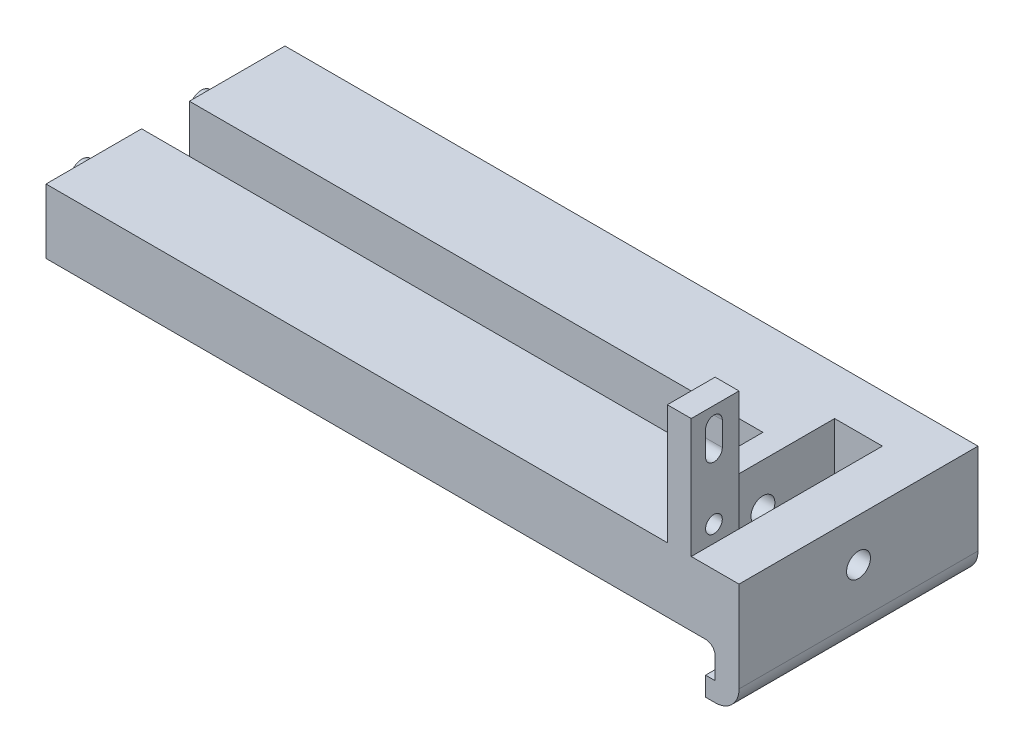
SolidWorks part; units mm, degrees
ref_plane "Front Plane" through (0, 0, 0) normal (0, 0, 1) x (1, 0, 0)
ref_plane "Top Plane" through (0, 0, 0) normal (0, 1, 0) x (1, 0, 0)
ref_plane "Right Plane" through (0, 0, 0) normal (1, 0, 0) x (0, 0, -1)
sketch "Sketch1" plane through (0, 0, 0) normal (0, 0, 1) x (1, 0, 0)
  line L0 (0, 0) -> (-140, 0)
  line L1 (-140, 0) -> (-140, 13.5)
  line L2 (-140, 13.5) -> (0, 13.5)
  line L3 (0, 13.5) -> (0, 0)
  dimension "D1" = 140
  dimension "D2" = 13.5
extrude "Boss-Extrude1" add sketch "Sketch1" along normal blind 50
sketch "Sketch2" plane through (-140, 0, 0) normal (-1, 0, 0) x (0, 0, 1)
  line L0 (50, 13.5) -> (50, 0) construction
  line L1 (12.5, 6.75) -> (25, 6.75) construction
  line L2 (25, 6.75) -> (37.5, 6.75) construction
  line L3 (37.5, 6.75) -> (50, 6.75) construction
  line L4 (0, 6.75) -> (12.5, 6.75) construction
  line L5 (0, 13.5) -> (0, 0) construction
  circle A0 centre (12.5, 6.75) radius 2.5
  circle A2 centre (37.5, 6.75) radius 2.5
  point P9 (50, 6.75)
  dimension "D1" = 5
  dimension "D2" = 5
extrude "Boss-Extrude2" add sketch "Sketch2" along normal blind 5
sketch "Sketch6" plane through (0, 0, 0) normal (1, 0, 0) x (0, 0, -1)
  line L0 (-50, 0) -> (-50, 13.5) construction
  line L1 (0, 13.5) -> (-50, 13.5)
  line L2 (0, 13.5) -> (0, -10.5)
  line L3 (0, -10.5) -> (-50, -10.5)
  line L4 (-50, 13.5) -> (-50, -10.5)
  dimension "D1" = 24
extrude "Boss-Extrude4" add sketch "Sketch6" along normal blind 5
sketch "Sketch4" plane through (0, 13.5, 0) normal (0, 1, 0) x (1, 0, 0)
  line L1 (-5, -40) -> (-15, -40)
  line L2 (-5, -40) -> (-5, -10)
  line L3 (-5, -10) -> (-15, -10)
  line L4 (-15, -40) -> (-15, -10)
  line L7 (5, 0) -> (-140, 0) construction
  line L8 (5, -50) -> (-140, -50) construction
  line L9 (5, 0) -> (5, -50) construction
  dimension "D1" = 10
  dimension "D2" = 10
  dimension "D3" = 10
  dimension "D4" = 10
extrude "Cut-Extrude1" cut sketch "Sketch4" against normal through all both and the other way through all
sketch "Sketch7" plane through (5, 0, 0) normal (1, 0, 0) x (0, 0, -1)
  line L0 (0, 13.5) -> (-50, 13.5) construction
  line L1 (-50, 13.5) -> (-50, -10.5) construction
  circle A0 centre (-25, 4.5) radius 2.5
  dimension "D3" = 5
  dimension "D1" = 9
  dimension "D2" = 25
extrude "Cut-Extrude3" cut sketch "Sketch7" against normal blind 35
sketch "Sketch8" plane through (0, 0, 0) normal (-1, 0, 0) x (0, 0, 1)
  line L0 (0, -10.5) -> (0, 0) construction
  line L1 (0, -6.5) -> (50, -6.5)
  line L2 (0, -6.5) -> (0, -10.5)
  line L3 (0, -10.5) -> (50, -10.5)
  line L4 (50, -6.5) -> (50, -10.5)
  line L5 (50, 0) -> (50, -10.5) construction
  dimension "D1" = 4
  dimension "D2" = 6.5
extrude "Boss-Extrude5" add sketch "Sketch8" along normal blind 2
sketch "Sketch9" plane through (0, 13.5, 0) normal (0, 1, 0) x (1, 0, 0)
  line L0 (-140, -50) -> (-140, 0) construction
  line L1 (-140, -30) -> (-20, -30)
  line L2 (-140, -30) -> (-140, -20)
  line L3 (-140, -20) -> (-20, -20)
  line L4 (-20, -30) -> (-20, -20)
  line L5 (-15, -40) -> (-15, -10) construction
  line L6 (-140, -25) -> (-15, -25) construction
  point P8 (-20, -25)
  dimension "D1" = 5
  dimension "D2" = 10
extrude "Cut-Extrude4" cut sketch "Sketch9" against normal blind 15
sketch "Sketch10" plane through (0, 13.5, 0) normal (0, 1, 0) x (1, 0, 0)
  line L0 (5, -50) -> (-140, -50) construction
  line L1 (-5, -40) -> (-10, -40)
  line L2 (-5, -40) -> (-5, -50)
  line L3 (-5, -50) -> (-10, -50)
  line L4 (-10, -40) -> (-10, -50)
  dimension "D1" = 5
extrude "Boss-Extrude6" add sketch "Sketch10" along normal blind 25
sketch "Sketch13" plane through (-10, 0, 0) normal (-1, 0, 0) x (0, 0, 1)
  line L0 (45.25, 13.5) -> (45.25, 36.75) construction
  line L1 (43.5, 30) -> (43.5, 35)
  line L3 (47, 35) -> (47, 30)
  line L4 (40, 13.5) -> (50, 13.5) construction
  line L7 (50, 38.5) -> (50, 13.5) construction
  circle A0 centre (45.25, 17) radius 1.75
  arc A1 (43.5, 30) -> (47, 30) centre (45.25, 30) ccw
  arc A2 (43.5, 35) -> (47, 35) centre (45.25, 35) cw
  point P16 (0, 0)
  dimension "D1" = 3.5
  dimension "D2" = 4.75
  dimension "D3" = 5
  dimension "D4" = 3.5
  dimension "D5" = 13
extrude "Cut-Extrude5" cut sketch "Sketch13" against normal through all both and the other way through all
fillet "Fillet1" radius 2 1 edges at (0, 0, 25)
fillet "Fillet2" radius 5 1 edges at (5, -10.5, 25)
